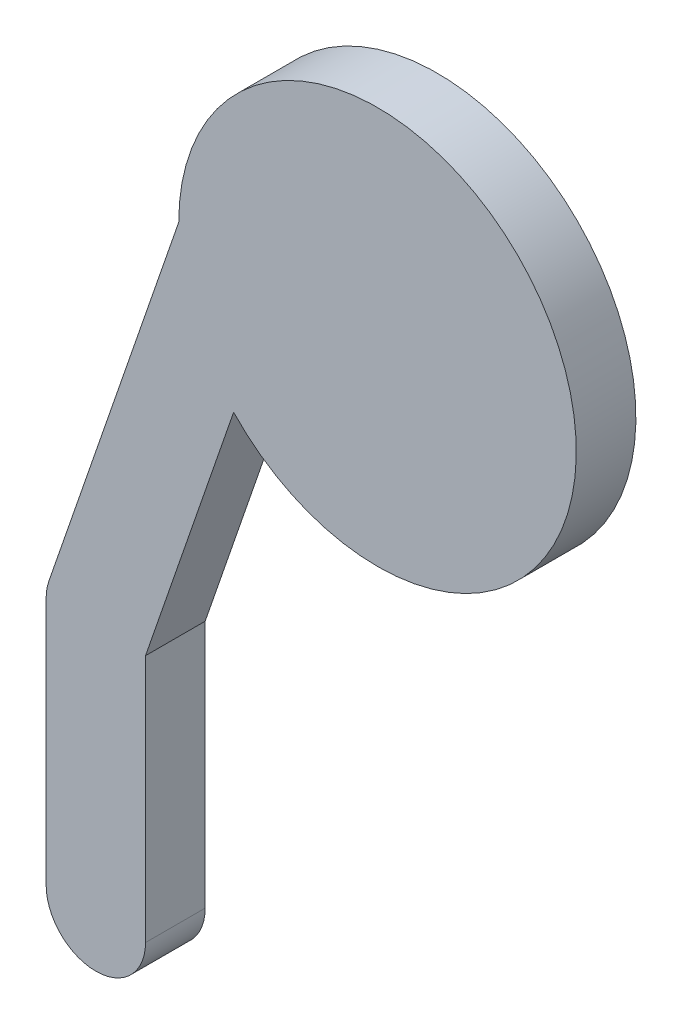
SolidWorks part; units mm, degrees
ref_plane "Front Plane" through (0, 0, 0) normal (1, 0, 0) x (0, 1, 0)
ref_plane "Top Plane" through (0, 0, 0) normal (0, 0, 1) x (0, 1, 0)
ref_plane "Right Plane" through (0, 0, 0) normal (0, 1, 0) x (-1, 0, 0)
sketch "Sketch1" plane through (0, 0, 0) normal (0, 0, 1) x (0, 1, 0)
  line L0 (0, 5) -> (25, 5)
  line L1 (0, -5) -> (25, -5)
  line L2 (64.4387, -8.3419) -> (26.6334, 4.7257)
  line L3 (25, -5) -> (50.6415, -13.8631)
  line L4 (0, 0) -> (64.4387, -28.3419) construction
  arc A2 (0, 5) -> (0, -5) centre (0, 0) ccw
  arc A3 (26.6334, 4.7257) -> (25, 5) centre (25, 0) ccw
  arc A4 (50.6415, -13.8631) -> (64.4387, -8.3419) centre (64.4387, -28.3419) ccw
  dimension "D1" = 10
  dimension "D2" = 10
  dimension "D3" = 40
  dimension "D4" = 25
  dimension "D5" = 25
  dimension "D6" = 40
extrude "Boss-Extrude1" add sketch "Sketch1" along normal blind 6
sketch "Sketch2" plane through (0, 0, 0) normal (0, 0, -1) x (1, 0, 0)
  circle A0 centre (0, 0) radius 2.8048
extrude "Cut-Extrude1" cut sketch "Sketch2" against normal blind 3
